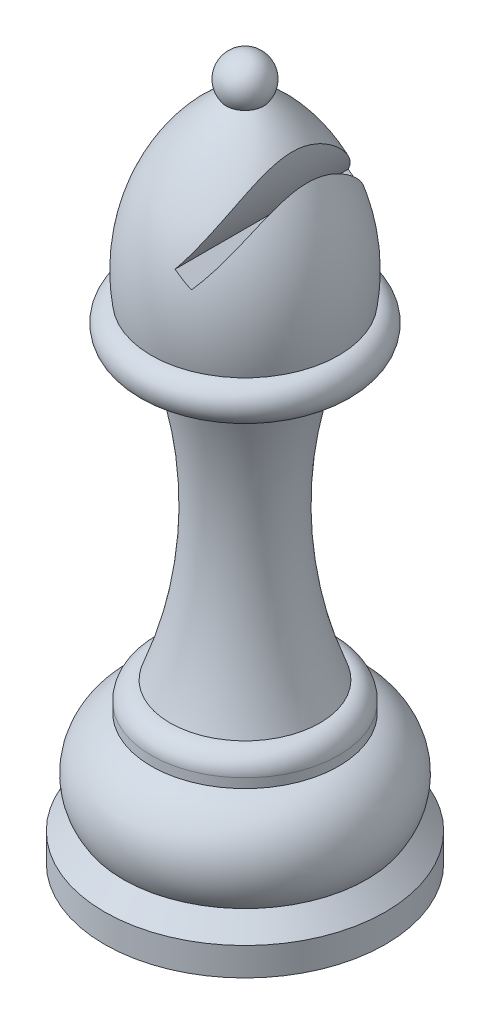
SolidWorks part; units mm, degrees
ref_plane "Ön Düzlem" through (0, 0, 0) normal (0, 0, 1) x (1, 0, 0)
ref_plane "Üst Düzlem" through (0, 0, 0) normal (0, 1, 0) x (1, 0, 0)
ref_plane "Sağ Düzlem" through (0, 0, 0) normal (1, 0, 0) x (0, 0, -1)
sketch "Çizim1" plane through (0, 0, 0) normal (0, 0, 1) x (1, 0, 0)
  line L1 (0, 9.9422) -> (0, -116.0168) construction
  line L2 (-15, -72.51) -> (0, -72.51)
  line L3 (-10, -24.52) -> (-7.5, -24.52)
  line L4 (0, -72.51) -> (0, 2.5)
  line L7 (-10, -57.54) -> (-10, -58.54)
  line L11 (-15, -72.51) -> (-15, -69.51)
  line L12 (-13, -67.51) -> (-15, -69.51)
  arc A0 (0, 2.5) -> (-2, -1.5) centre (0, 0) ccw
  arc A1 (-2, -1.5) -> (-10, -20.56) centre (9.7882, -17.6567) ccw
  arc A2 (-10, -20.56) -> (-10, -24.52) centre (-9.7179, -22.54) ccw
  arc A3 (-7.5, -24.52) -> (-8, -55.54) centre (-49.9864, -39.3492) cw
  arc A5 (-8, -55.54) -> (-10, -57.54) centre (-8, -57.54) ccw
  arc A6 (-10, -58.54) -> (-13, -67.51) centre (-7.9981, -64.1962) ccw
  dimension "D2" = 2.5
  dimension "D5" = 2
  dimension "D7" = 20
  dimension "D11" = 45
  dimension "D14" = 2
  dimension "D24" = 6
  dimension "D3" = 15
  dimension "D6" = 10
  dimension "D9" = 10
  dimension "D13" = 7.5
  dimension "D18" = 2
revolve "Döndür4" add sketch "Çizim1" angle 360 about L1
sketch "Çizim2" plane through (0, 0, 0) normal (0, 0, 1) x (1, 0, 0)
  line L0 (1.7768, -12.0706) -> (3.393, -13.2486)
  arc A1 (3.393, -13.2486) -> (6.653, -6.2686) centre (-8.5136, -3.4364) ccw
  arc A2 (1.7768, -12.0706) -> (5.0272, -4.2214) centre (-12.7588, -1.4537) ccw
  arc A4 (5.0272, -4.2214) -> (6.653, -6.2686) centre (-9.7882, -17.6567) cw
extrude "Kes-Ekstrüzyon1" cut sketch "Çizim2" against normal through all and the other way through all
